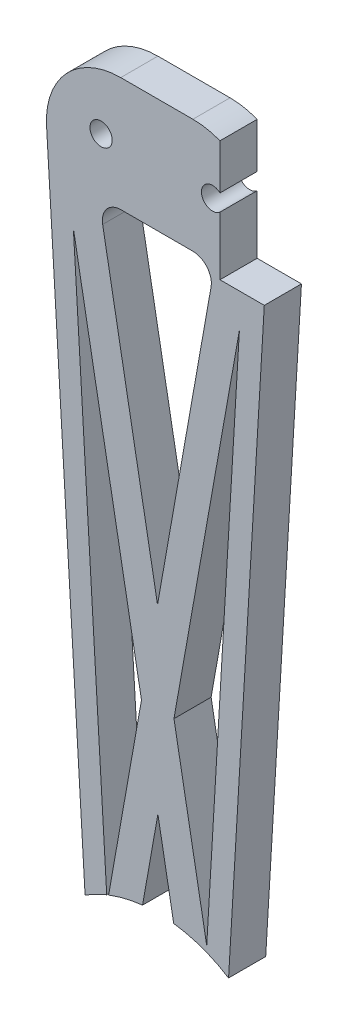
SolidWorks part; units mm, degrees
ref_plane "Front Plane" through (0, 0, 0) normal (0, 0, 1) x (1, 0, 0)
ref_plane "Top Plane" through (0, 0, 0) normal (0, 1, 0) x (1, 0, 0)
ref_plane "Right Plane" through (0, 0, 0) normal (1, 0, 0) x (0, 0, -1)
sketch "Sketch1" plane through (0, 0, 0) normal (0, 0, 1) x (1, 0, 0)
  line L0 (-30, 0) -> (30, 0)
  line L1 (0, 0) -> (15, 0)
  line L2 (55, 0) -> (-55, 0) construction
  line L3 (0, 0) -> (0, -210)
  line L4 (0, -44.7868) -> (0, 44.7868) construction
  line L5 (0, 0) -> (30, 0)
  line L6 (0, 0) -> (-30, 0)
  line L7 (0, 0) -> (-15, 0)
  line L8 (-6, -215) -> (6, -215)
  line L9 (-6, -215) -> (-6, -205)
  line L10 (-6, -205) -> (6, -205)
  line L11 (6, -215) -> (6, -205)
  line L12 (-6, -215) -> (6, -205) construction
  line L13 (-6, -205) -> (6, -215) construction
  line L14 (0, 0) -> (0, 15)
  line L15 (-30, 0) -> (-17.5, -210)
  line L16 (-30, 0) -> (30, 0)
  line L17 (-30, 0) -> (-30, 15.7704)
  line L18 (-30, 15.7704) -> (30, 15.7704)
  line L19 (30, 0) -> (30, 15.7704)
  line L20 (30, 0) -> (17.5, -210)
  circle A0 centre (15, 0) radius 3
  circle A1 centre (-15, 0) radius 3
  circle A2 centre (0, -210) radius 17.5
  point P4 (0, 0)
  dimension "D7" = 6
  dimension "D9" = 6
  dimension "D11" = 35
  dimension "D1" = 210
  dimension "D2" = 30
  dimension "D3" = 30
  dimension "D4" = 10
  dimension "D5" = 12
  dimension "D6" = 15
  dimension "D8" = 15
  dimension "D10" = 15
extrude "Boss-Extrude2" add sketch "Sketch1" along normal blind 10
fillet "Fillet1" radius 20 1 edges at (-30, 15.7704, 5)
fillet "Fillet2" radius 20 1 edges at (30, 15.7704, 5)
sketch "Sketch4" plane through (0, 0, 10) normal (0, 0, 1) x (1, 0, 0)
  line L0 (-29.3398, -11.0918) -> (-23.3398, -11.0918)
  line L1 (-29.6775, -5.418) -> (-17.5, -210) construction
  line L2 (29.3911, -10.23) -> (23.3911, -10.23)
  line L3 (29.6775, -5.418) -> (17.5, -210) construction
  line L4 (-18.3824, -195.1758) -> (-12.3824, -195.1758)
  line L5 (18.3824, -195.1758) -> (12.3824, -195.1758)
  line L6 (-12.3824, -195.1758) -> (-23.5439, -7.6624)
  line L7 (23.3911, -7.6624) -> (11.6198, -205.4193)
  line L8 (-22.9543, -15) -> (22.9543, -15)
  line L9 (-8.4362, -200.1287) -> (-16.4545, -196.0413)
  line L10 (9.2183, -200.015) -> (17.2308, -195.9163)
  line L11 (9.2183, -200.015) -> (-24.5465, -14.245)
  line L12 (17.2308, -195.9163) -> (-16.534, -10.1463)
  line L13 (-24.5465, -14.245) -> (-16.534, -10.1463)
  line L14 (-8.4362, -200.1287) -> (24.4903, -14.4152)
  line L15 (-16.4545, -196.0413) -> (16.472, -10.3277)
  line L16 (24.4903, -14.4152) -> (16.472, -10.3277)
  circle A0 centre (0, -210) radius 17.5
  circle A1 centre (15, 0) radius 15
  point P25 (0, -15)
  dimension "D5" = 15
  dimension "D1" = 6
  dimension "D2" = 6
  dimension "D3" = 6
  dimension "D4" = 6
  dimension "D6" = 9
  dimension "D7" = 9
extrude "Cut-Extrude1" cut sketch "Sketch4" against normal blind 10 contours L12 L15 L8 | L6 L15 L11 | L14 L12 L7 | A0 L11 L14
fillet "Fillet3" radius 5 4 edges at (8.2256, -194.5537, 5) (-7.3724, -194.1287, 5) (-15.6518, -15, 5) (15.6436, -15, 5)
sketch "Sketch5" plane through (0, 0, 10) normal (0, 0, 1) x (1, 0, 0)
  line L0 (15, 0) -> (30, 0)
  line L1 (55, 0) -> (-55, 0) construction
  line L2 (30, 0) -> (30, -20)
  line L3 (0, -175.7959) -> (34.2041, -175.7959)
  line L5 (30, -20) -> (30, 16.6458)
  line L6 (30, 16.6458) -> (17, 16.6458)
  line L8 (0, -175.7959) -> (-19.536, -175.7959)
  line L9 (-29.6775, -5.418) -> (-17.5, -210) construction
  line L11 (17, -20) -> (17, -18)
  line L13 (17, -18) -> (30.4933, -18)
  line L14 (17, -18) -> (17, 17.0491)
  line L15 (17, 17.0491) -> (30.4933, 17.0491)
  line L16 (30.4933, -18) -> (30.4933, 17.0491)
  circle A0 centre (0, -210) radius 30
  circle A1 centre (0, -210) radius 34.2041
  circle A2 centre (0, -210) radius 36
  line M1 (17.5, -210) -> (29.6775, -5.418)
  arc M2 (29.6775, -5.418) -> (9.7128, 15.7704) centre (9.7128, -4.2296) ccw
  line M5 (-29.6775, -5.418) -> (-17.5, -210)
  arc M6 (-17.5, -210) -> (17.5, -210) centre (0, -210) ccw
  circle M7 centre (15, 0) radius 3
  line M9 (-6, -215) -> (-6, -205)
  line M10 (-6, -205) -> (6, -205)
  line M11 (6, -205) -> (6, -215)
  line M12 (6, -215) -> (-6, -215)
  line M18 (0.2916, -150.9016) -> (6.7953, -186.6842)
  arc M19 (6.7953, -186.6842) -> (1.459, -192.5609) centre (1.8759, -187.5783) cw
  arc M20 (1.459, -192.5609) -> (-0.8744, -192.5219) centre (0, -210) ccw
  arc M21 (-0.8744, -192.5219) -> (-6.0474, -186.6552) centre (-1.1242, -187.5281) cw
  line M22 (-6.0474, -186.6552) -> (0.2916, -150.9016)
  line M26 (-4.1342, -126.5515) -> (-13.3673, -178.6289)
  line M27 (-13.3673, -178.6289) -> (-22.473, -25.6531)
  dimension "D3" = 60
  dimension "D4" = 36
  dimension "D1" = 15
  dimension "D2" = 20
  dimension "D5" = 2
extrude "Cut-Extrude3" cut sketch "Sketch5" against normal blind 10 contours L8 A2 A1 M26 M22 | A2 A1 M27 M5 | A2 L8 M22 | L3 A2 M18 | A2 L3 A1 M1 M18 | A1 A0 M1 M18 | A0 M1 M18 M19 M20 M21 M22 M5 M6 M12 M9 M10 M11 | A1 A0 M22 M26 M27 M5 | L14 L0 M7 M2 | L14 L13 L0 M1 M2 M7
